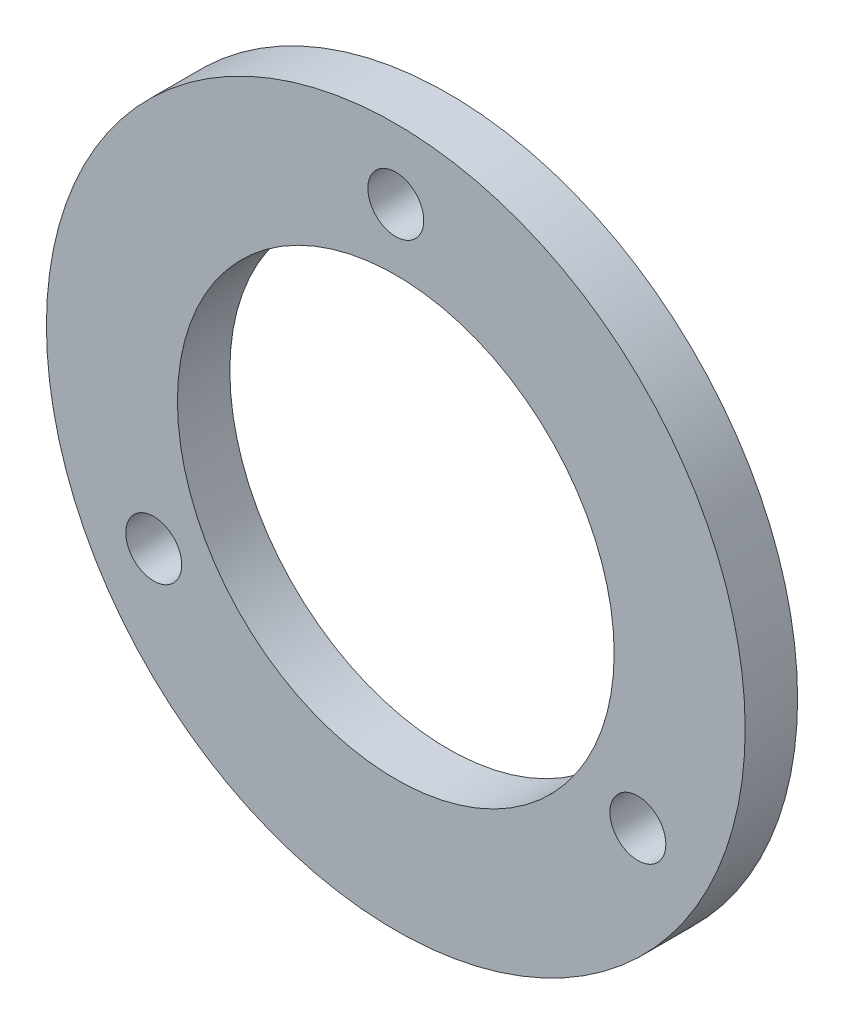
SolidWorks part; units mm, degrees
material "3240环氧板"
ref_plane "前视基准面" through (0, 0, 0) normal (0, 0, 1) x (1, 0, 0)
ref_plane "上视基准面" through (0, 0, 0) normal (0, 1, 0) x (1, 0, 0)
ref_plane "右视基准面" through (0, 0, 0) normal (1, 0, 0) x (0, 0, -1)
other "Configuration Table"
sketch "草图1" plane through (0, 0, 0) normal (0, 0, 1) x (1, 0, 0)
  circle A0 centre (-61.2854, -189.5649) radius 20
  circle A2 centre (-61.2854, -189.5649) radius 12.5
  circle A3 centre (-61.2854, -173.5649) radius 1.6
  circle A4 centre (-47.429, -197.5649) radius 1.6
  circle A5 centre (-75.1418, -197.5649) radius 1.6
  dimension "D1" = 40
  dimension "D2" = 25
  dimension "D3" = 3.2
  dimension "D4" = 3.2
  dimension "D5" = 3.2
extrude "凸台-拉伸1" add sketch "草图1" along normal blind 3
